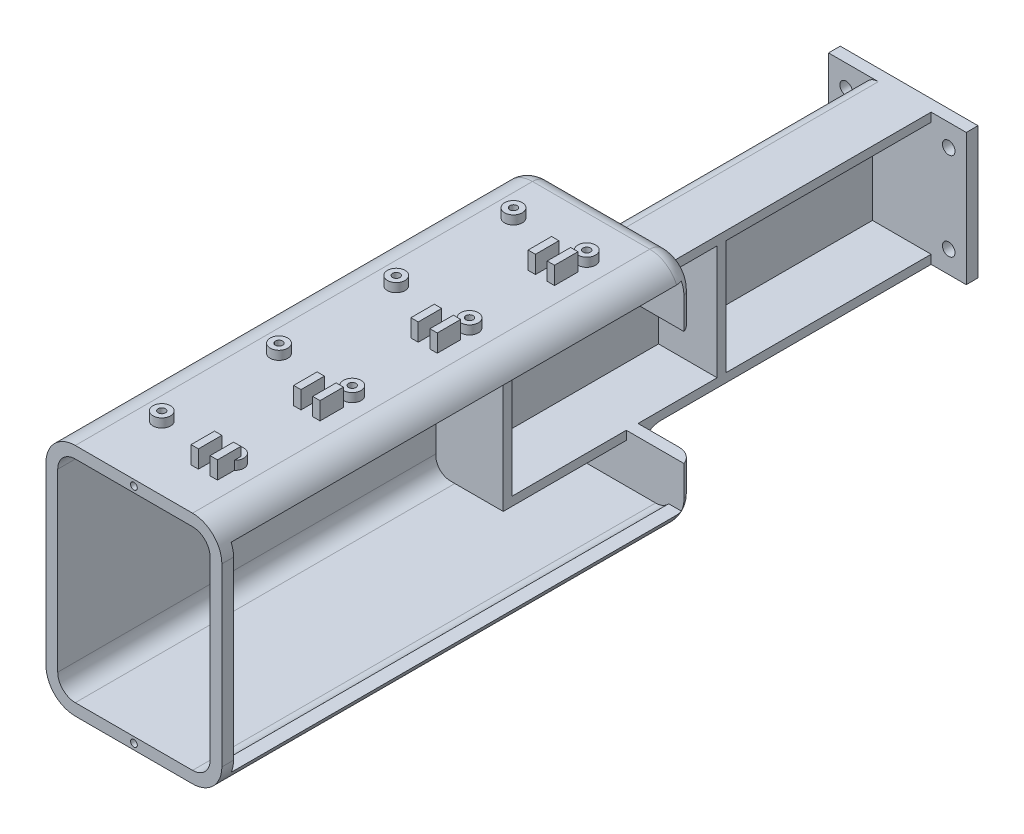
SolidWorks part; units mm, degrees
ref_plane "Front Plane" through (0, 0, 0) normal (0, 0, 1) x (1, 0, 0)
ref_plane "Top Plane" through (0, 0, 0) normal (0, 1, 0) x (1, 0, 0)
ref_plane "Right Plane" through (0, 0, 0) normal (1, 0, 0) x (0, 0, -1)
sketch "草圖1" plane through (0, 0, 0) normal (0, 0, 1) x (1, 0, 0)
  line L0 (-13, -22.5) -> (10, -22.5)
  line L1 (10, -22.5) -> (10, -19.5)
  line L2 (10, -19.5) -> (-10, -19.5)
  line L3 (-10, -19.5) -> (-10, 19.5)
  line L4 (-10, 19.5) -> (10, 19.5)
  line L5 (10, 19.5) -> (10, 22.5)
  line L6 (10, 22.5) -> (-13, 22.5)
  line L7 (-13, 22.5) -> (-13, -22.5)
extrude "填料-伸長1" add sketch "草圖1" along normal blind 150
fillet "圓角1" radius 5 2 edges at (-13, 22.5, 75) (-13, -22.5, 75)
sketch "草圖2" plane through (0, 0, 0) normal (0, 0, 1) x (1, 0, 0)
  line L0 (-25, -22.5) -> (22, -22.5)
  line L1 (22, -22.5) -> (22, 22.5)
  line L2 (22, 22.5) -> (-25, 22.5)
  line L3 (-25, 22.5) -> (-25, -22.5)
  circle A0 centre (-19, 15) radius 2.15
  circle A1 centre (-19, -15) radius 2.15
  circle A2 centre (16, 15) radius 2.15
  circle A3 centre (16, -15) radius 2.15
extrude "填料-伸長2" add sketch "草圖2" along normal blind 4
sketch "草圖3" plane through (0, 0, 0) normal (0, 0, 1) x (1, 0, 0)
  line L0 (-10.5, -20) -> (10, -20)
  line L1 (10, -20) -> (10, 20)
  line L2 (10, 20) -> (-10.5, 20)
  line L3 (-10.5, 20) -> (-10.5, -20)
extrude "填料-伸長3" add sketch "草圖3" along normal blind 3 from offset 74
sketch "草圖4" plane through (0, 0, 0) normal (0, 0, 1) x (1, 0, 0)
  line L0 (-10.5, -20) -> (10, -20)
  line L1 (10, -20) -> (10, 20)
  line L2 (10, 20) -> (-10.5, 20)
  line L3 (-10.5, 20) -> (-10.5, -20)
extrude "填料-伸長4" add sketch "草圖4" along normal blind 3 from offset 147
sketch "草圖5" plane through (0, 0, 0) normal (0, 0, 1) x (1, 0, 0)
  line L0 (30, -30) -> (30, 30)
  line L1 (20, 40) -> (-20, 40)
  line L2 (-30, 30) -> (-30, -30)
  line L3 (-20, -40) -> (20, -40)
  arc A0 (20, -40) -> (30, -30) centre (20, -30) ccw
  arc A1 (30, 30) -> (20, 40) centre (20, 30) ccw
  arc A2 (-20, 40) -> (-30, 30) centre (-20, 30) ccw
  arc A3 (-30, -30) -> (-20, -40) centre (-20, -30) ccw
extrude "填料-伸長5" add sketch "草圖5" along normal blind 4 from offset 104
sketch "草圖6" plane through (0, 0, 0) normal (0, 0, 1) x (1, 0, 0)
  line L0 (30, -30) -> (30, 30)
  line L1 (20, 40) -> (-20, 40)
  line L2 (-30, 30) -> (-30, -30)
  line L3 (-20, -40) -> (20, -40)
  line L4 (26, -30) -> (26, 30)
  line L5 (20, 36) -> (-20, 36)
  line L6 (-26, 30) -> (-26, -30)
  line L7 (-20, -36) -> (20, -36)
  arc A0 (20, -40) -> (30, -30) centre (20, -30) ccw
  arc A1 (30, 30) -> (20, 40) centre (20, 30) ccw
  arc A2 (-20, 40) -> (-30, 30) centre (-20, 30) ccw
  arc A3 (-30, -30) -> (-20, -40) centre (-20, -30) ccw
  arc A4 (20, -36) -> (26, -30) centre (20, -30) ccw
  arc A5 (26, 30) -> (20, 36) centre (20, 30) ccw
  arc A6 (-20, 36) -> (-26, 30) centre (-20, 30) ccw
  arc A7 (-26, -30) -> (-20, -36) centre (-20, -30) ccw
extrude "填料-伸長6" add sketch "草圖6" along normal blind 158 from offset 108
fillet "圓角2" radius 8 5 edges at (1, -22.5, 104) (-13, 0, 104) (-11.5355, 21.0355, 104) (1, 22.5, 104) (-11.5355, -21.0355, 104)
fillet "圓角3" radius 6 8 edges at (27.0711, -37.0711, 104) (30, 0, 104) (27.0711, 37.0711, 104) (0, 40, 104) (-27.0711, 37.0711, 104) (-30, 0, 104) (-27.0711, -37.0711, 104) (0, -40, 104)
sketch "草圖7" plane through (0, 0, 0) normal (0, 0, 1) x (1, 0, 0)
  line L0 (-10, -19.5) -> (35, -19.5)
  line L1 (35, -19.5) -> (35, 19.5)
  line L2 (35, 19.5) -> (-10, 19.5)
  line L3 (-10, 19.5) -> (-10, -19.5)
extrude "除料-伸長1" cut sketch "草圖7" along normal blind 70 from offset 77
sketch "草圖8" plane through (0, 0, 0) normal (0, 0, 1) x (1, 0, 0)
  line L0 (24, -34) -> (35, -34)
  line L1 (35, -34) -> (35, 34)
  line L2 (35, 34) -> (24, 34)
  line L3 (24, 34) -> (24, -34)
extrude "除料-伸長2" cut sketch "草圖8" along normal blind 154 from offset 108
sketch "草圖9" plane through (0, 0, 0) normal (0, 0, 1) x (1, 0, 0)
  circle A0 centre (0, 38) radius 1.15
  circle A1 centre (0, -38) radius 1.15
extrude "除料-伸長3" cut sketch "草圖9" along normal blind 8 from offset 258
sketch "草圖10" plane through (0, 0, 0) normal (0, 1, 0) x (1, 0, 0)
  circle A0 centre (-12.5, -124) radius 3
  circle A1 centre (-12.5, -124) radius 1.25
  circle A2 centre (-12.5, -164) radius 3
  circle A3 centre (-12.5, -164) radius 1.25
  circle A4 centre (-12.5, -204) radius 3
  circle A5 centre (-12.5, -204) radius 1.25
  circle A6 centre (-12.5, -244) radius 3
  circle A7 centre (-12.5, -244) radius 1.25
  circle A8 centre (12.5, -124) radius 3
  circle A9 centre (12.5, -124) radius 1.25
  circle A10 centre (12.5, -164) radius 3
  circle A11 centre (12.5, -164) radius 1.25
  circle A12 centre (12.5, -204) radius 3
  circle A13 centre (12.5, -204) radius 1.25
  circle A14 centre (12.5, -244) radius 3
  circle A15 centre (12.5, -244) radius 1.25
extrude "填料-伸長7" add sketch "草圖10" along normal blind 3 from offset 40
sketch "草圖11" plane through (0, 0, 0) normal (0, 1, 0) x (1, 0, 0)
  circle A0 centre (-12.5, -124) radius 3
  circle A1 centre (-12.5, -124) radius 1.25
  circle A2 centre (-12.5, -164) radius 3
  circle A3 centre (-12.5, -164) radius 1.25
  circle A4 centre (-12.5, -204) radius 3
  circle A5 centre (-12.5, -204) radius 1.25
  circle A6 centre (-12.5, -244) radius 3
  circle A7 centre (-12.5, -244) radius 1.25
  circle A8 centre (12.5, -124) radius 3
  circle A9 centre (12.5, -124) radius 1.25
  circle A10 centre (12.5, -164) radius 3
  circle A11 centre (12.5, -164) radius 1.25
  circle A12 centre (12.5, -204) radius 3
  circle A13 centre (12.5, -204) radius 1.25
  circle A14 centre (12.5, -244) radius 3
  circle A15 centre (12.5, -244) radius 1.25
extrude "填料-伸長8" add sketch "草圖11" against normal blind 3 from offset 40
sketch "草圖12" plane through (0, 0, 0) normal (1, 0, 0) x (0, 0, -1)
  circle A0 centre (-124, -15) radius 3
  circle A1 centre (-124, -15) radius 1.25
  circle A2 centre (-164, -15) radius 3
  circle A3 centre (-164, -15) radius 1.25
  circle A4 centre (-204, -15) radius 3
  circle A5 centre (-204, -15) radius 1.25
  circle A6 centre (-244, -15) radius 3
  circle A7 centre (-244, -15) radius 1.25
  circle A8 centre (-124, 15) radius 3
  circle A9 centre (-124, 15) radius 1.25
  circle A10 centre (-164, 15) radius 3
  circle A11 centre (-164, 15) radius 1.25
  circle A12 centre (-204, 15) radius 3
  circle A13 centre (-204, 15) radius 1.25
  circle A14 centre (-244, 15) radius 3
  circle A15 centre (-244, 15) radius 1.25
extrude "填料-伸長9" add sketch "草圖12" against normal blind 3 from offset 30
sketch "草圖13" plane through (0, 0, 0) normal (0, 1, 0) x (1, 0, 0)
  line L0 (5.5, -129) -> (8, -129)
  line L1 (8, -129) -> (8, -137)
  line L2 (8, -137) -> (5.5, -137)
  line L3 (5.5, -137) -> (5.5, -129)
  line L4 (12, -129) -> (14.5, -129)
  line L5 (14.5, -129) -> (14.5, -137)
  line L6 (14.5, -137) -> (12, -137)
  line L7 (12, -137) -> (12, -129)
  line L8 (5.5, -169) -> (8, -169)
  line L9 (8, -169) -> (8, -177)
  line L10 (8, -177) -> (5.5, -177)
  line L11 (5.5, -177) -> (5.5, -169)
  line L12 (12, -169) -> (14.5, -169)
  line L13 (14.5, -169) -> (14.5, -177)
  line L14 (14.5, -177) -> (12, -177)
  line L15 (12, -177) -> (12, -169)
  line L16 (5.5, -209) -> (8, -209)
  line L17 (8, -209) -> (8, -217)
  line L18 (8, -217) -> (5.5, -217)
  line L19 (5.5, -217) -> (5.5, -209)
  line L20 (12, -209) -> (14.5, -209)
  line L21 (14.5, -209) -> (14.5, -217)
  line L22 (14.5, -217) -> (12, -217)
  line L23 (12, -217) -> (12, -209)
  line L24 (5.5, -244) -> (8, -244)
  line L25 (8, -244) -> (8, -252)
  line L26 (8, -252) -> (5.5, -252)
  line L27 (5.5, -252) -> (5.5, -244)
  line L28 (12, -244) -> (14.5, -244)
  line L29 (14.5, -244) -> (14.5, -252)
  line L30 (14.5, -252) -> (12, -252)
  line L31 (12, -252) -> (12, -244)
extrude "填料-伸長10" add sketch "草圖13" along normal blind 6 from offset 40
sketch "草圖14" plane through (0, 0, 0) normal (0, 1, 0) x (1, 0, 0)
  line L0 (5.5, -129) -> (8, -129)
  line L1 (8, -129) -> (8, -137)
  line L2 (8, -137) -> (5.5, -137)
  line L3 (5.5, -137) -> (5.5, -129)
  line L4 (12, -129) -> (14.5, -129)
  line L5 (14.5, -129) -> (14.5, -137)
  line L6 (14.5, -137) -> (12, -137)
  line L7 (12, -137) -> (12, -129)
  line L8 (5.5, -169) -> (8, -169)
  line L9 (8, -169) -> (8, -177)
  line L10 (8, -177) -> (5.5, -177)
  line L11 (5.5, -177) -> (5.5, -169)
  line L12 (12, -169) -> (14.5, -169)
  line L13 (14.5, -169) -> (14.5, -177)
  line L14 (14.5, -177) -> (12, -177)
  line L15 (12, -177) -> (12, -169)
  line L16 (5.5, -209) -> (8, -209)
  line L17 (8, -209) -> (8, -217)
  line L18 (8, -217) -> (5.5, -217)
  line L19 (5.5, -217) -> (5.5, -209)
  line L20 (12, -209) -> (14.5, -209)
  line L21 (14.5, -209) -> (14.5, -217)
  line L22 (14.5, -217) -> (12, -217)
  line L23 (12, -217) -> (12, -209)
  line L24 (5.5, -244) -> (8, -244)
  line L25 (8, -244) -> (8, -252)
  line L26 (8, -252) -> (5.5, -252)
  line L27 (5.5, -252) -> (5.5, -244)
  line L28 (12, -244) -> (14.5, -244)
  line L29 (14.5, -244) -> (14.5, -252)
  line L30 (14.5, -252) -> (12, -252)
  line L31 (12, -252) -> (12, -244)
extrude "填料-伸長11" add sketch "草圖14" against normal blind 6 from offset 40
